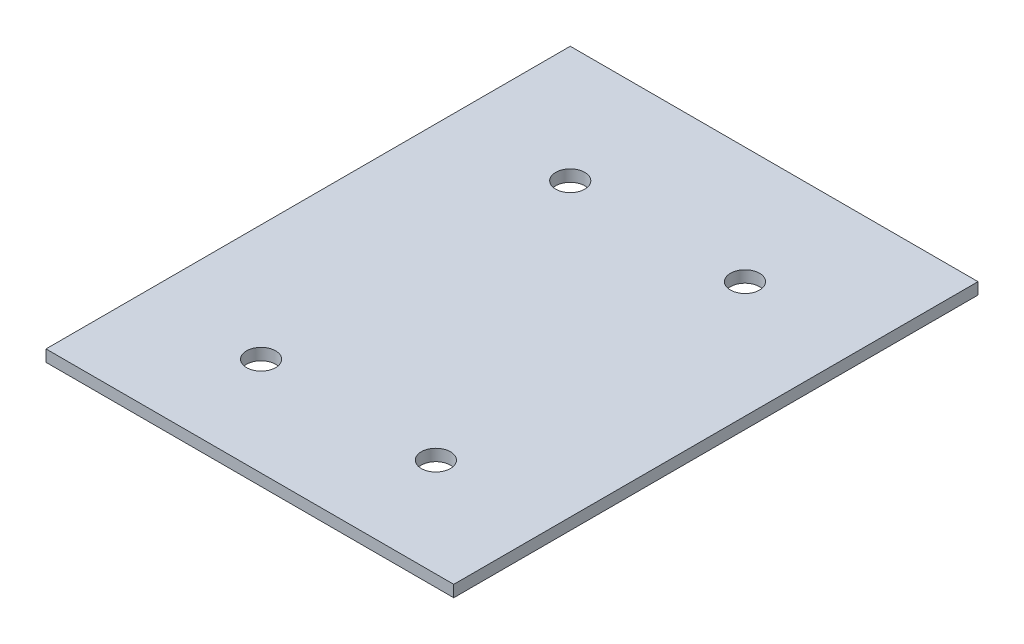
SolidWorks part; units mm, degrees
ref_plane "Front Plane" through (0, 0, 0) normal (0, 0, 1) x (1, 0, 0)
ref_plane "Top Plane" through (0, 0, 0) normal (0, 1, 0) x (1, 0, 0)
ref_plane "Right Plane" through (0, 0, 0) normal (1, 0, 0) x (0, 0, -1)
sketch "Sketch1" plane through (0, 0, 0) normal (0, 1, 0) x (1, 0, 0)
  line L1 (-35, 45) -> (35, 45)
  line L2 (-35, 45) -> (-35, -45)
  line L3 (-35, -45) -> (35, -45)
  line L4 (35, 45) -> (35, -45)
  line L5 (-35, 45) -> (35, -45) construction
  line L6 (-35, -45) -> (35, 45) construction
  circle A0 centre (-15, 25) radius 2.5
  circle A1 centre (15, 25) radius 2.5
  circle A2 centre (-15, -28.0714) radius 2.5
  circle A3 centre (15, -28.0714) radius 2.5
  point P0 (0, 0)
  point P14 (0, 0)
  point P15 (0, 0)
  point P16 (0, 0)
  point P17 (0, 0)
  dimension "D4" = 30
  dimension "D6" = 53.0714
  dimension "D7" = 5
  dimension "D1" = 70
  dimension "D2" = 90
  dimension "D3" = 20
  dimension "D5" = 20
extrude "Boss-Extrude1" add sketch "Sketch1" along normal blind 2
